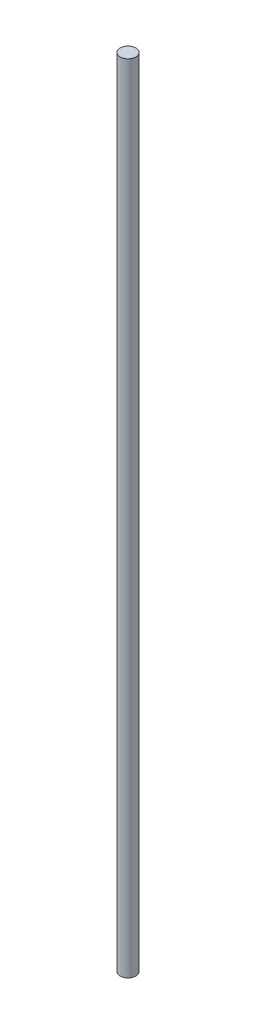
SolidWorks part; units mm, degrees
ref_plane "Front Plane" through (0, 0, 0) normal (0, 0, 1) x (1, 0, 0)
ref_plane "Top Plane" through (0, 0, 0) normal (0, 1, 0) x (1, 0, 0)
ref_plane "Right Plane" through (0, 0, 0) normal (1, 0, 0) x (0, 0, -1)
sketch "Sketch1" plane through (0, 0, 0) normal (0, 1, 0) x (1, 0, 0)
  circle A0 centre (0, 0) radius 4
extrude "Boss-Extrude1" add sketch "Sketch1" along normal blind 405
